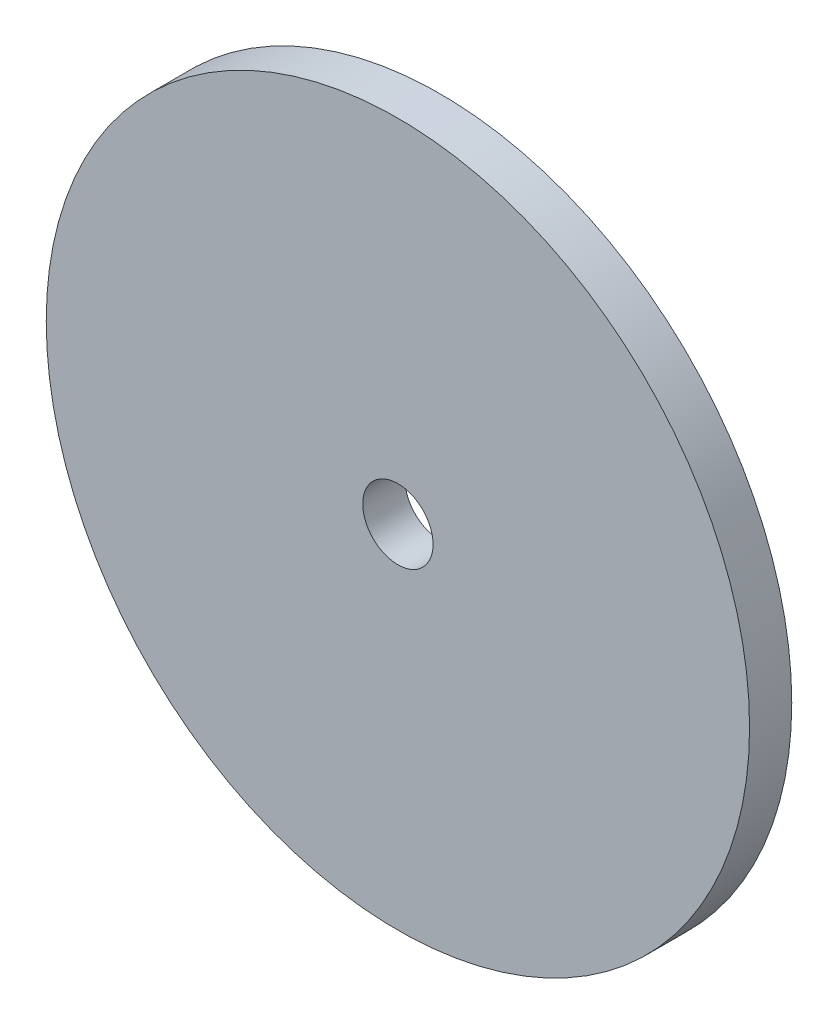
SolidWorks part; units mm, degrees
ref_plane "Front Plane" through (0, 0, 0) normal (1, 0, 0) x (0, 1, 0)
ref_plane "Top Plane" through (0, 0, 0) normal (0, 0, 1) x (0, 1, 0)
ref_plane "Right Plane" through (0, 0, 0) normal (0, 1, 0) x (-1, 0, 0)
sketch "Sketch1" plane through (0, 0, 0) normal (0, 0, 1) x (0, 1, 0)
  circle A0 centre (0, 0) radius 25
  dimension "D1" = 50
extrude "Boss-Extrude1" add sketch "Sketch1" along normal blind 3
sketch "Sketch3" plane through (0, 0, 0) normal (0, 0, 1) x (0, 1, 0)
  circle A0 centre (0, 0) radius 2.5
  dimension "D1" = 5
extrude "Cut-Extrude1" cut sketch "Sketch3" along normal through all both and the other way through all
